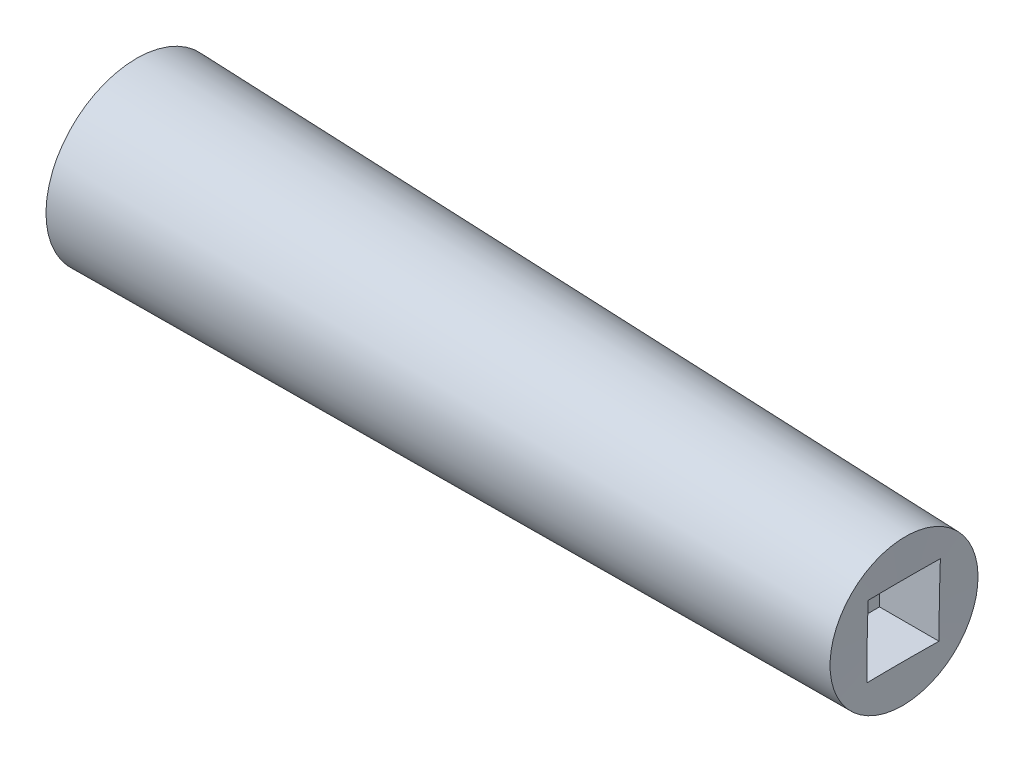
SolidWorks part; units mm, degrees
ref_plane "Front Plane" through (0, 0, 0) normal (0, 0, 1) x (1, 0, 0)
ref_plane "Top Plane" through (0, 0, 0) normal (0, 1, 0) x (1, 0, 0)
ref_plane "Right Plane" through (0, 0, 0) normal (1, 0, 0) x (0, 0, -1)
sketch "Sketch1" plane through (0, 0, 0) normal (0, 0, 1) x (1, 0, 0)
  line L1 (165.1, 0) -> (165.1, 15.875)
  line L2 (0, 0) -> (0, 19.05)
  line L3 (0, 19.05) -> (165.1, 15.875)
  line L4 (0, 0) -> (12.7, 0)
  line L5 (12.7, 0) -> (165.1, 0)
  dimension "D1" = 15.875
  dimension "D2" = 19.05
  dimension "D3" = 12.7
revolve "Revolve1" add sketch "Sketch1" angle 360 about L3
ref_plane "Plane1" through (165.1, 0, 0) normal (1, 0, 0) x (0, 0, -1)
sketch "Sketch2" plane through (165.1, 0, 0) normal (1, 0, 0) x (0, 0, -1)
  line L1 (7.747, 8.128) -> (-7.747, 8.128)
  line L2 (7.747, 8.128) -> (7.747, 23.622)
  line L3 (7.747, 23.622) -> (-7.747, 23.622)
  line L4 (-7.747, 8.128) -> (-7.747, 23.622)
  line L5 (7.747, 8.128) -> (-7.747, 23.622) construction
  line L6 (7.747, 23.622) -> (-7.747, 8.128) construction
  point P0 (0, 15.875)
  dimension "D1" = 15.494
  dimension "D2" = 15.494
extrude "Cut-Extrude1" cut sketch "Sketch2" against normal mid plane 25.4
